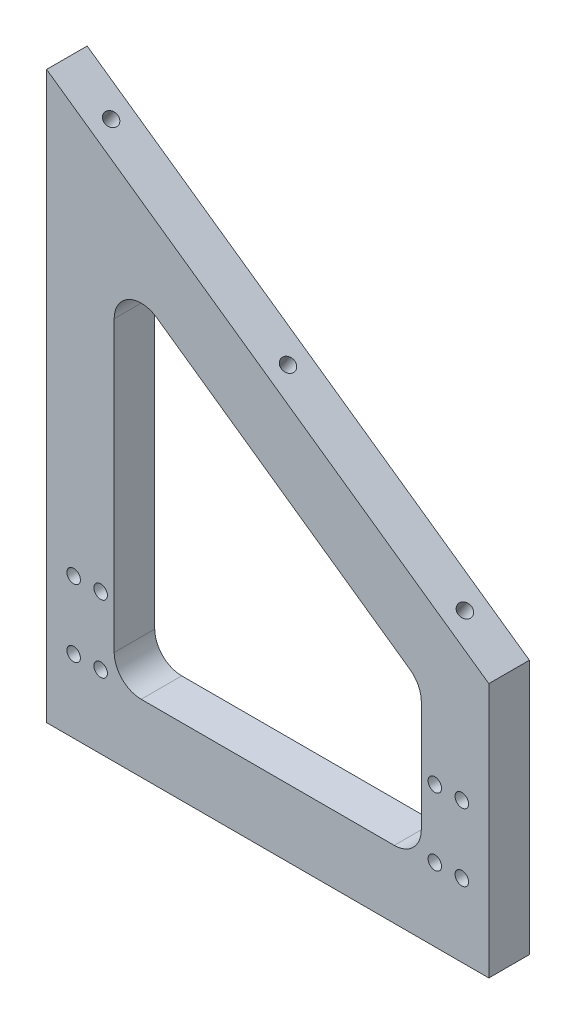
SolidWorks part; units mm, degrees
ref_plane "前视基准面" through (0, 0, 0) normal (0, 0, 1) x (1, 0, 0)
ref_plane "上视基准面" through (0, 0, 0) normal (0, 1, 0) x (1, 0, 0)
ref_plane "右视基准面" through (0, 0, 0) normal (1, 0, 0) x (0, 0, -1)
sketch "草图1" plane through (0, 0, 0) normal (0, 0, 1) x (1, 0, 0)
  line L0 (0, 0) -> (163.6299, 0)
  line L1 (163.6299, 0) -> (163.6299, 94.33)
  line L2 (163.6299, 94.33) -> (0, 209.3311)
  line L3 (0, 209.3311) -> (0, 0)
  dimension "D1" = 125.1
  dimension "D2" = 200
  dimension "D3" = 94.33
extrude "凸台-拉伸1" add sketch "草图1" along normal blind 15
sketch "草图2" plane through (0, 0, 15) normal (0, 0, 1) x (1, 0, 0)
  line L0 (25, 161.204) -> (25, 25)
  line L1 (25, 25) -> (138.6299, 25)
  line L2 (138.6299, 25) -> (138.6299, 81.3435)
  line L3 (138.6299, 81.3435) -> (25, 161.204)
  line L4 (0, 0) -> (163.6299, 0) construction
  line L5 (0, 209.3311) -> (0, 0) construction
  line L6 (163.6299, 0) -> (163.6299, 94.33) construction
  line L7 (163.6299, 94.33) -> (0, 209.3311) construction
  dimension "D1" = 125.1
  dimension "D2" = 25
  dimension "D3" = 25
  dimension "D4" = 25
  dimension "D5" = 25
extrude "切除-拉伸1" cut sketch "草图2" against normal through all
fillet "圆角1" radius 10 4 edges at (25, 25, 7.5) (138.6299, 25, 7.5) (138.6299, 81.3435, 7.5) (25, 161.204, 7.5)
hole_wizard "M6 螺纹孔1" positions "草图4" profile "草图3" tap size "M6" standard "ISO"
sketch "草图4" plane through (0, 0, 0) normal (0, -1, 0) x (1, 0, 0)
  line L0 (0, 0) -> (163.6299, 0) construction
  line L1 (0, 15) -> (0, 0) construction
  point P0 (30, 7.5)
  dimension "D1" = 7.5
  dimension "D2" = 30
sketch "草图3" plane through (30, 0, 7.5) normal (1, 0, 0) x (0, 0, -1)
  line L0 (0, 0) -> (0, 16.5022)
  line L1 (0, 16.5022) -> (2.5, 15)
  line L2 (2.5, 15) -> (2.5, 0)
  line L5 (2.5, 0) -> (0, 0)
  line L10 (0, 16.5022) -> (-2.5, 15) construction
  line L11 (0, -6.35) -> (0, 107.95) construction
  dimension "螺纹孔钻头直径" = 5
  dimension "螺纹孔钻头深度" = 15
  dimension "导头角度" = 118
cosmetic thread "孔螺蚊线1" parameters "D1"=12, "D2"=6
pattern_linear "阵列(线性)1" count 3 spacing 50 along (1, 0, 0) of "M6 螺纹孔1"
hole_wizard "M6 螺纹孔2" positions "草图6" profile "草图5" tap size "M6" standard "ISO"
sketch "草图6" plane through (98.4778, 140.1197, 0) normal (0.575, 0.8181, 0) x (-0.8181, 0.575, 0)
  line L0 (-79.6335, 0) -> (120.3665, 0) construction
  line L1 (-79.6335, 15) -> (-79.6335, 0) construction
  point P0 (-59.6335, 7.5)
  dimension "D1" = 7.5
  dimension "D2" = 20
sketch "草图5" plane through (147.2669, 105.8301, 7.5) normal (0, 0, 1) x (-0.8181, 0.575, 0)
  line L0 (0, 0) -> (0, 16.5022)
  line L1 (0, 16.5022) -> (2.5, 15)
  line L2 (2.5, 15) -> (2.5, 0)
  line L5 (2.5, 0) -> (0, 0)
  line L10 (0, 16.5022) -> (-2.5, 15) construction
  line L11 (0, -6.35) -> (0, 107.95) construction
  dimension "螺纹孔钻头直径" = 5
  dimension "螺纹孔钻头深度" = 15
  dimension "导头角度" = 118
cosmetic thread "孔螺蚊线2" parameters "D1"=12, "D2"=6
pattern_linear "阵列(线性)2" count 3 spacing 80 along (-0.8181, 0.575, 0) of "M6 螺纹孔2"
hole_wizard "M6 螺纹孔3" positions "草图8" profile "草图7" tap size "M6" standard "ISO" end condition through all
sketch "草图8" plane through (0, 0, 15) normal (0, 0, 1) x (1, 0, 0)
  circle A0 centre (20, 27) radius 2.75 construction
  point P0 (20, 27)
  point P3 (20, 52)
  point P6 (10, 52)
  point P9 (10, 27)
  point P12 (143.6299, 52)
  point P15 (153.6299, 52)
  point P18 (143.6299, 27)
  point P21 (153.6299, 27)
sketch "草图7" plane through (20, 27, 15) normal (1, 0, 0) x (0, -1, 0)
  line L0 (0, 0) -> (0, 15)
  line L1 (0, 15) -> (2.5, 15)
  line L2 (2.5, 15) -> (2.5, 0)
  line L5 (2.5, 0) -> (0, 0)
  line L11 (0, -6.35) -> (0, 107.95) construction
  dimension "通孔螺纹孔钻头直径" = 5
  dimension "通孔螺纹孔钻头深度" = 15
cosmetic thread "孔螺蚊线3" parameters "D2"=6
cosmetic thread "孔螺蚊线4" parameters "D2"=6
cosmetic thread "孔螺蚊线5" parameters "D2"=6
cosmetic thread "孔螺蚊线6" parameters "D2"=6
cosmetic thread "孔螺蚊线7" parameters "D2"=6
cosmetic thread "孔螺蚊线8" parameters "D2"=6
cosmetic thread "孔螺蚊线9" parameters "D2"=6
cosmetic thread "孔螺蚊线10" parameters "D2"=6
